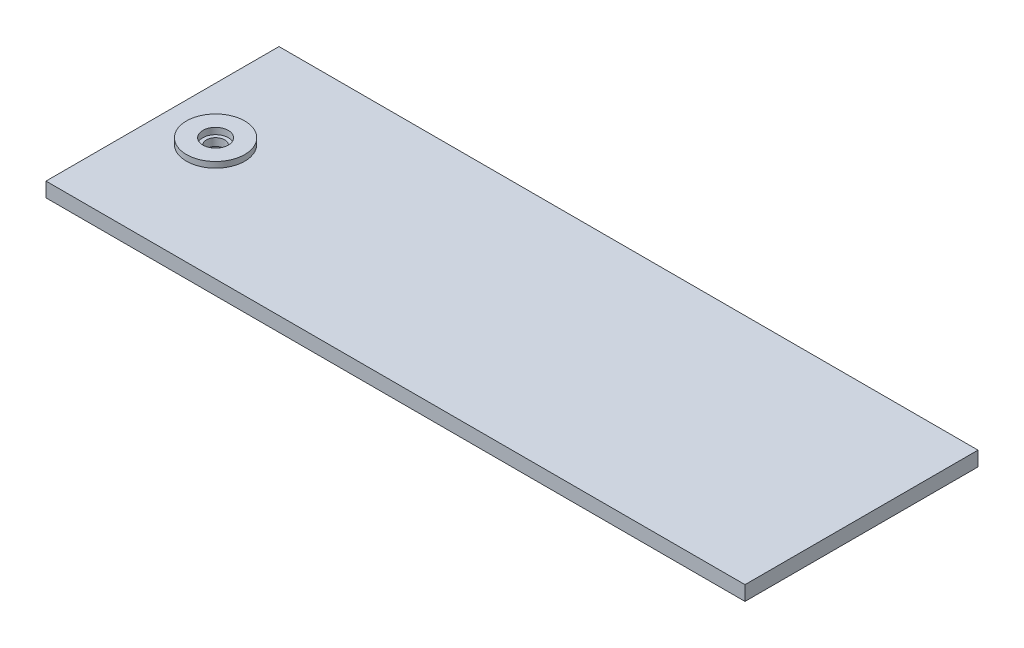
SolidWorks part; units mm, degrees
ref_plane "Front Plane" through (0, 0, 0) normal (0, 0, 1) x (1, 0, 0)
ref_plane "Top Plane" through (0, 0, 0) normal (0, 1, 0) x (1, 0, 0)
ref_plane "Right Plane" through (0, 0, 0) normal (1, 0, 0) x (0, 0, -1)
sketch "Sketch1" plane through (0, 0, 0) normal (0, 1, 0) x (1, 0, 0)
  line L1 (-304.8, -101.6) -> (304.8, -101.6)
  line L2 (-304.8, -101.6) -> (-304.8, 101.6)
  line L3 (-304.8, 101.6) -> (304.8, 101.6)
  line L4 (304.8, -101.6) -> (304.8, 101.6)
  line L5 (-304.8, -101.6) -> (304.8, 101.6) construction
  line L6 (-304.8, 101.6) -> (304.8, -101.6) construction
  point P0 (0, 0)
  dimension "D1" = 609.6
  dimension "D2" = 203.2
extrude "Boss-Extrude1" add sketch "Sketch1" along normal blind 12.7
sketch "Sketch2" plane through (0, 12.7, 0) normal (0, 1, 0) x (1, 0, 0)
  circle A0 centre (-258.5106, 0) radius 25.4
  dimension "D1" = 50.8
extrude "Boss-Extrude3" add sketch "Sketch2" along normal blind 5.08
sketch "Sketch9" plane through (0, 17.78, 0) normal (0, 1, 0) x (1, 0, 0)
  circle A0 centre (-258.5106, 0) radius 11.1125
extrude "Cut-Extrude4" cut sketch "Sketch9" against normal blind 5.5562
sketch "Sketch10" plane through (0, 0, 0) normal (0, -1, 0) x (-1, 0, 0)
  circle A0 centre (258.5106, 0) radius 11.1125
extrude "Cut-Extrude5" cut sketch "Sketch10" against normal blind 5.5562
sketch "Sketch11" plane through (0, 12.2238, 0) normal (0, 1, 0) x (1, 0, 0)
  circle A0 centre (-258.5106, 0) radius 7.9375
extrude "Cut-Extrude6" cut sketch "Sketch11" against normal through all
